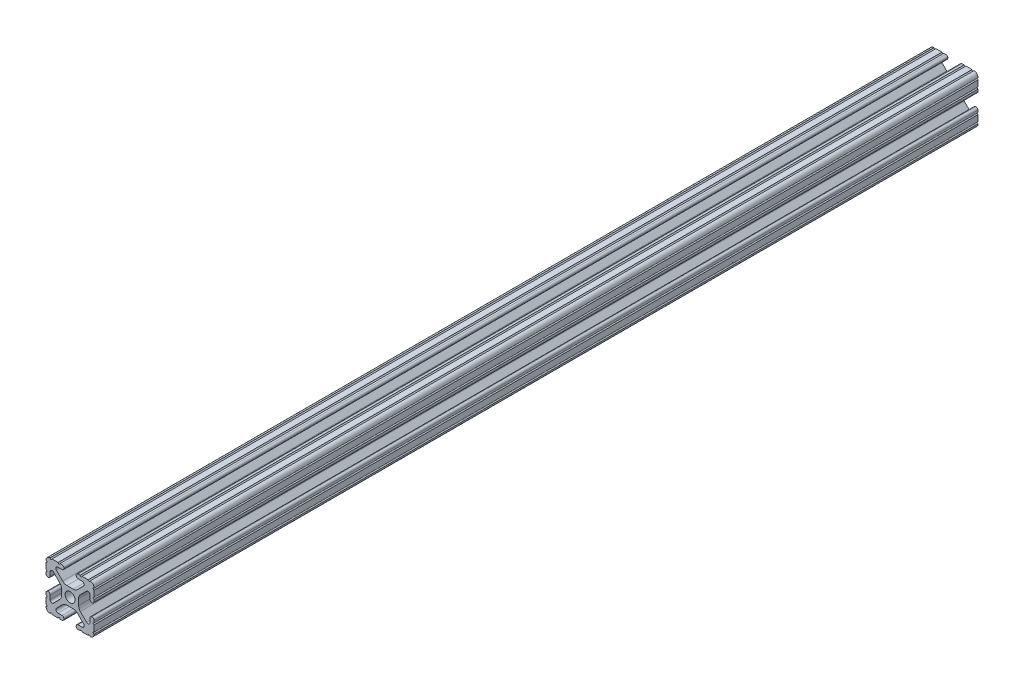
SolidWorks part; units mm, degrees
ref_plane "Front Plane" through (0, 0, 0) normal (0, 0, 1) x (1, 0, 0)
ref_plane "Top Plane" through (0, 0, 0) normal (0, 1, 0) x (1, 0, 0)
ref_plane "Right Plane" through (0, 0, 0) normal (1, 0, 0) x (0, 0, -1)
sketch "Sketch1" plane through (0, 0, 0) normal (0, 0, 1) x (1, 0, 0)
  line L0 (-7.207, 8.7244) -> (-3.8983, 5.4232)
  line L1 (-4.2875, 10.4902) -> (-6.4768, 10.4902)
  line L2 (-3.2385, 11.651) -> (-3.2385, 11.5392)
  line L3 (-5.3171, 12.7) -> (-4.2875, 12.7)
  line L4 (0, 13.4005) -> (0, -14.8534) construction
  line L5 (12.7, 0) -> (-13.9989, 0) construction
  line L6 (-9.5504, 12.7) -> (-6.3331, 12.7)
  line L7 (-12.7, 6.3331) -> (-12.7, 9.5504)
  line L8 (-12.7, 4.2875) -> (-12.7, 5.3171)
  line L9 (-11.5392, 3.2385) -> (-11.651, 3.2385)
  line L10 (-10.4902, 6.4021) -> (-10.4902, 4.2875)
  line L11 (-5.441, 3.8408) -> (-8.7371, 7.1294)
  line L12 (-4.5085, -1.5932) -> (-4.5085, 1.5932)
  line L13 (-1.7093, -4.4958) -> (1.7093, -4.4958)
  line L14 (3.9523, -5.4237) -> (7.1797, -8.6452)
  line L15 (6.4164, -10.4902) -> (4.2875, -10.4902)
  line L16 (3.2385, -11.5392) -> (3.2385, -11.651)
  line L17 (4.2875, -12.7) -> (5.3171, -12.7)
  line L18 (6.3331, -12.7) -> (9.5504, -12.7)
  line L19 (12.7, -9.5504) -> (12.7, -6.3331)
  line L20 (12.7, -5.3171) -> (12.7, -4.2875)
  line L21 (11.651, -3.2385) -> (11.5392, -3.2385)
  line L22 (10.4902, -4.2875) -> (10.4902, -6.4021)
  line L23 (8.7371, -7.1294) -> (5.441, -3.8408)
  line L24 (4.5085, -1.5932) -> (4.5085, 1.5932)
  line L25 (5.441, 3.8408) -> (8.7371, 7.1294)
  line L26 (10.4902, 6.4021) -> (10.4902, 4.2875)
  line L27 (11.5392, 3.2385) -> (11.651, 3.2385)
  line L28 (12.7, 4.2875) -> (12.7, 5.3171)
  line L29 (12.7, 6.3331) -> (12.7, 9.5504)
  line L30 (9.5504, 12.7) -> (6.3331, 12.7)
  line L31 (5.3171, 12.7) -> (4.2875, 12.7)
  line L32 (3.2385, 11.651) -> (3.2385, 11.5392)
  line L33 (4.2875, 10.4902) -> (6.4768, 10.4902)
  line L34 (7.207, 8.7244) -> (3.8983, 5.4232)
  line L35 (1.6558, 4.4958) -> (-1.6558, 4.4958)
  line L36 (-8.7371, -7.1294) -> (-5.441, -3.8408)
  line L37 (-10.4902, -4.2875) -> (-10.4902, -6.4021)
  line L38 (-11.651, -3.2385) -> (-11.5392, -3.2385)
  line L39 (-12.7, -5.3171) -> (-12.7, -4.2875)
  line L40 (-12.7, -9.5504) -> (-12.7, -6.3331)
  line L41 (-6.3331, -12.7) -> (-9.5504, -12.7)
  line L42 (-4.2875, -12.7) -> (-5.3171, -12.7)
  line L43 (-3.2385, -11.5392) -> (-3.2385, -11.651)
  line L44 (-6.4164, -10.4902) -> (-4.2875, -10.4902)
  line L45 (-3.9523, -5.4237) -> (-7.1797, -8.6452)
  arc A0 (-7.207, 8.7244) -> (-6.4768, 10.4902) centre (-6.4768, 9.4563) cw
  arc A1 (-3.2385, 11.5392) -> (-4.2875, 10.4902) centre (-4.2875, 11.5392) cw
  arc A2 (-4.2875, 12.7) -> (-3.2385, 11.651) centre (-4.2875, 11.651) cw
  arc A3 (-5.3171, 12.7) -> (-6.3331, 12.7) centre (-5.8251, 12.7) cw
  arc A4 (-9.5504, 12.7) -> (-10.5664, 12.6998) centre (-10.0584, 12.7) cw
  arc A5 (-12.6998, 10.5664) -> (-10.5664, 12.6998) centre (-10.5918, 10.5918) cw
  arc A6 (-12.6998, 10.5664) -> (-12.7, 9.5504) centre (-12.7, 10.0584) cw
  arc A7 (-12.7, 6.3331) -> (-12.7, 5.3171) centre (-12.7, 5.8251) cw
  arc A8 (-11.651, 3.2385) -> (-12.7, 4.2875) centre (-11.651, 4.2875) cw
  arc A9 (-10.4902, 4.2875) -> (-11.5392, 3.2385) centre (-11.5392, 4.2875) cw
  circle A10 centre (0, 0) radius 2.6035
  arc A11 (-10.4902, 6.4021) -> (-8.7371, 7.1294) centre (-9.4628, 6.4021) cw
  arc A12 (-5.441, 3.8408) -> (-4.5085, 1.5932) centre (-7.6835, 1.5932) cw
  arc A13 (-4.5085, -1.5932) -> (-5.441, -3.8408) centre (-7.6835, -1.5932) cw
  arc A14 (-8.7371, -7.1294) -> (-10.4902, -6.4021) centre (-9.4628, -6.4021) cw
  arc A15 (-1.7093, -4.4958) -> (-3.9523, -5.4237) centre (-1.7093, -7.6708) ccw
  arc A16 (3.9523, -5.4237) -> (1.7093, -4.4958) centre (1.7093, -7.6708) ccw
  arc A17 (6.4164, -10.4902) -> (7.1797, -8.6452) centre (6.4164, -9.4098) ccw
  arc A18 (4.2875, -10.4902) -> (3.2385, -11.5392) centre (4.2875, -11.5392) ccw
  arc A19 (3.2385, -11.651) -> (4.2875, -12.7) centre (4.2875, -11.651) ccw
  arc A20 (6.3331, -12.7) -> (5.3171, -12.7) centre (5.8251, -12.7) ccw
  arc A21 (10.5664, -12.6998) -> (9.5504, -12.7) centre (10.0584, -12.7) ccw
  arc A22 (10.5664, -12.6998) -> (12.6998, -10.5664) centre (10.5918, -10.5918) ccw
  arc A23 (12.7, -9.5504) -> (12.6998, -10.5664) centre (12.7, -10.0584) ccw
  arc A24 (12.7, -5.3171) -> (12.7, -6.3331) centre (12.7, -5.8251) ccw
  arc A25 (12.7, -4.2875) -> (11.651, -3.2385) centre (11.651, -4.2875) ccw
  arc A26 (11.5392, -3.2385) -> (10.4902, -4.2875) centre (11.5392, -4.2875) ccw
  arc A27 (8.7371, -7.1294) -> (10.4902, -6.4021) centre (9.4628, -6.4021) ccw
  arc A28 (4.5085, -1.5932) -> (5.441, -3.8408) centre (7.6835, -1.5932) ccw
  arc A29 (5.441, 3.8408) -> (4.5085, 1.5932) centre (7.6835, 1.5932) ccw
  arc A30 (10.4902, 6.4021) -> (8.7371, 7.1294) centre (9.4628, 6.4021) ccw
  arc A31 (10.4902, 4.2875) -> (11.5392, 3.2385) centre (11.5392, 4.2875) ccw
  arc A32 (11.651, 3.2385) -> (12.7, 4.2875) centre (11.651, 4.2875) ccw
  arc A33 (12.7, 6.3331) -> (12.7, 5.3171) centre (12.7, 5.8251) ccw
  arc A34 (12.6998, 10.5664) -> (12.7, 9.5504) centre (12.7, 10.0584) ccw
  arc A35 (12.6998, 10.5664) -> (10.5664, 12.6998) centre (10.5918, 10.5918) ccw
  arc A36 (9.5504, 12.7) -> (10.5664, 12.6998) centre (10.0584, 12.7) ccw
  arc A37 (5.3171, 12.7) -> (6.3331, 12.7) centre (5.8251, 12.7) ccw
  arc A38 (4.2875, 12.7) -> (3.2385, 11.651) centre (4.2875, 11.651) ccw
  arc A39 (3.2385, 11.5392) -> (4.2875, 10.4902) centre (4.2875, 11.5392) ccw
  arc A40 (7.207, 8.7244) -> (6.4768, 10.4902) centre (6.4768, 9.4563) ccw
  arc A41 (1.6558, 4.4958) -> (3.8983, 5.4232) centre (1.6558, 7.6708) ccw
  arc A42 (-1.6558, 4.4958) -> (-3.8983, 5.4232) centre (-1.6558, 7.6708) cw
  arc A43 (-11.5392, -3.2385) -> (-10.4902, -4.2875) centre (-11.5392, -4.2875) cw
  arc A44 (-12.7, -4.2875) -> (-11.651, -3.2385) centre (-11.651, -4.2875) cw
  arc A45 (-12.7, -5.3171) -> (-12.7, -6.3331) centre (-12.7, -5.8251) cw
  arc A46 (-12.7, -9.5504) -> (-12.6998, -10.5664) centre (-12.7, -10.0584) cw
  arc A47 (-10.5664, -12.6998) -> (-12.6998, -10.5664) centre (-10.5918, -10.5918) cw
  arc A48 (-10.5664, -12.6998) -> (-9.5504, -12.7) centre (-10.0584, -12.7) cw
  arc A49 (-6.3331, -12.7) -> (-5.3171, -12.7) centre (-5.8251, -12.7) cw
  arc A50 (-3.2385, -11.651) -> (-4.2875, -12.7) centre (-4.2875, -11.651) cw
  arc A51 (-4.2875, -10.4902) -> (-3.2385, -11.5392) centre (-4.2875, -11.5392) cw
  arc A52 (-6.4164, -10.4902) -> (-7.1797, -8.6452) centre (-6.4164, -9.4098) cw
  dimension "D1" = 5.207
  dimension "D9" = 14.859
  dimension "D2" = 25.4
  dimension "D3" = 12.7
  dimension "D4" = 6.477
  dimension "D5" = 8.2042
  dimension "D6" = 9.017
  dimension "D8" = 2.2098
  dimension "D10" = 2.2098
extrude "Extrude1" add sketch "Sketch1" against normal blind 466.725
